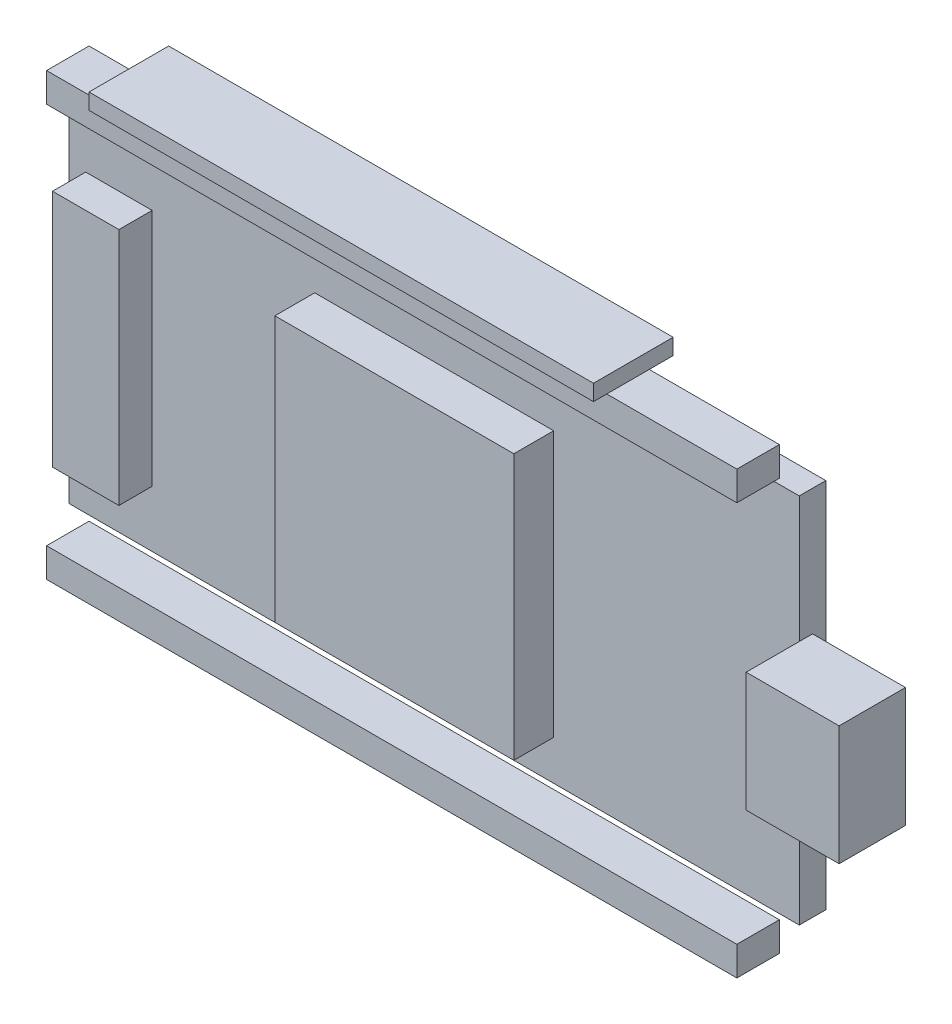
SolidWorks part; units mm, degrees
ref_plane "前视基准面" through (0, 0, 0) normal (0, 0, 1) x (1, 0, 0)
ref_plane "上视基准面" through (0, 0, 0) normal (0, 1, 0) x (1, 0, 0)
ref_plane "右视基准面" through (0, 0, 0) normal (1, 0, 0) x (0, 0, -1)
other "Configuration Table"
sketch "草图1" plane through (0, 0, 0) normal (0, 0, 1) x (1, 0, 0)
  line L1 (-27.5, -14) -> (27.5, -14)
  line L2 (-27.5, -14) -> (-27.5, 14)
  line L3 (-27.5, 14) -> (27.5, 14)
  line L4 (27.5, -14) -> (27.5, 14)
  line L5 (-27.5, -14) -> (27.5, 14) construction
  line L6 (-27.5, 14) -> (27.5, -14) construction
  point P0 (0, 0)
extrude "ESP32 DevKit PCB - approx 55 x 28 mm" add sketch "草图1" along normal blind 2 from offset 1 separate body
sketch "草图2" plane through (0, 0, 0) normal (0, 0, 1) x (1, 0, 0)
  line L1 (-8, -10) -> (10, -10)
  line L2 (-8, -10) -> (-8, 10)
  line L3 (-8, 10) -> (10, 10)
  line L4 (10, -10) -> (10, 10)
  line L5 (-8, -10) -> (10, 10) construction
  line L6 (-8, 10) -> (10, -10) construction
  point P0 (1, 0)
extrude "ESP-WROOM shield can" add sketch "草图2" along normal blind 3 from offset 2 separate body
sketch "草图3" plane through (0, 0, 0) normal (0, 0, 1) x (1, 0, 0)
  line L1 (27.5, -4.5) -> (34.5, -4.5)
  line L2 (27.5, -4.5) -> (27.5, 4.5)
  line L3 (27.5, 4.5) -> (34.5, 4.5)
  line L4 (34.5, -4.5) -> (34.5, 4.5)
  line L5 (27.5, -4.5) -> (34.5, 4.5) construction
  line L6 (27.5, 4.5) -> (34.5, -4.5) construction
  point P0 (31, 0)
extrude "micro USB connector" add sketch "草图3" along normal blind 5 separate body
sketch "草图4" plane through (0, 0, 0) normal (0, 0, 1) x (1, 0, 0)
  line L1 (-25.5, -9) -> (-20.5, -9)
  line L2 (-25.5, -9) -> (-25.5, 9)
  line L3 (-25.5, 9) -> (-20.5, 9)
  line L4 (-20.5, -9) -> (-20.5, 9)
  line L5 (-25.5, -9) -> (-20.5, 9) construction
  line L6 (-25.5, 9) -> (-20.5, -9) construction
  point P0 (-23, 0)
extrude "reset / boot button pair" add sketch "草图4" along normal blind 2.5 from offset 1.75 separate body
sketch "草图5" plane through (0, 0, 0) normal (0, 0, 1) x (1, 0, 0)
  line L1 (-26, -16.6) -> (26, -16.6)
  line L2 (-26, -16.6) -> (-26, -14.4)
  line L3 (-26, -14.4) -> (26, -14.4)
  line L4 (26, -16.6) -> (26, -14.4)
  line L5 (-26, -16.6) -> (26, -14.4) construction
  line L6 (-26, -14.4) -> (26, -16.6) construction
  point P0 (0, -15.5)
extrude "left pin header row" add sketch "草图5" along normal blind 3.2 from offset 1 separate body
sketch "草图6" plane through (0, 0, 0) normal (0, 0, 1) x (1, 0, 0)
  line L1 (-26, 14.4) -> (26, 14.4)
  line L2 (-26, 14.4) -> (-26, 16.6)
  line L3 (-26, 16.6) -> (26, 16.6)
  line L4 (26, 14.4) -> (26, 16.6)
  line L5 (-26, 14.4) -> (26, 16.6) construction
  line L6 (-26, 16.6) -> (26, 14.4) construction
  point P0 (0, 15.5)
extrude "right pin header row" add sketch "草图6" along normal blind 3.2 from offset 1 separate body
sketch "草图7" plane through (0, 0, 0) normal (0, 0, 1) x (1, 0, 0)
  line L1 (-19, 19.4) -> (19, 19.4)
  line L2 (-19, 19.4) -> (-19, 20.6)
  line L3 (-19, 20.6) -> (19, 20.6)
  line L4 (19, 19.4) -> (19, 20.6)
  line L5 (-19, 19.4) -> (19, 20.6) construction
  line L6 (-19, 20.6) -> (19, 19.4) construction
  point P0 (0, 20)
extrude "esp32 label plate - ESP32 55x28" add sketch "草图7" along normal blind 6 from offset 2 separate body
